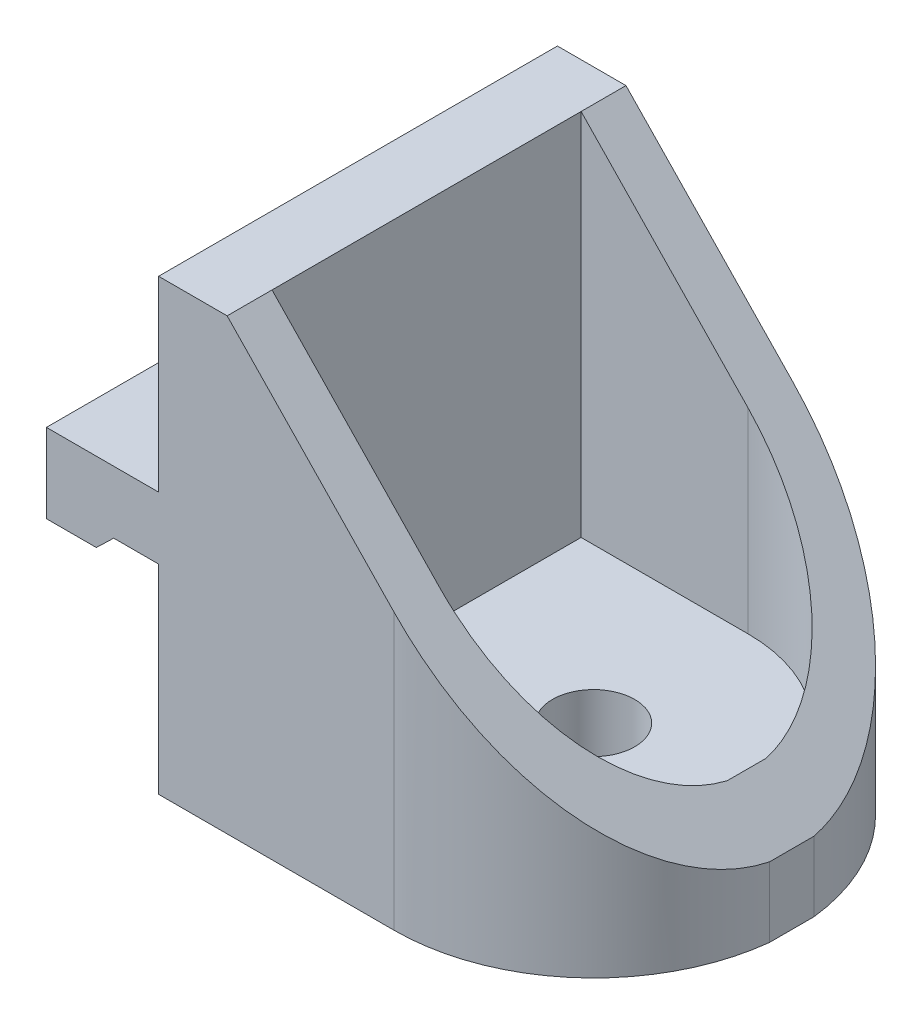
SolidWorks part; units mm, degrees
ref_plane "Front Plane" through (0, 0, 0) normal (0, 0, 1) x (1, 0, 0)
ref_plane "Top Plane" through (0, 0, 0) normal (0, 1, 0) x (1, 0, 0)
ref_plane "Right Plane" through (0, 0, 0) normal (1, 0, 0) x (0, 0, -1)
sketch "Sketch1" plane through (0, 0, 0) normal (0, 0, 1) x (1, 0, 0)
  line L0 (15.9, 0) -> (-18.9, 0)
  line L1 (-18.9, 0) -> (-18.9, 16)
  line L7 (-18.9, 21) -> (-18.9, 36)
  line L8 (-18.9, 36) -> (-13.4, 36)
  line L9 (-13.4, 36) -> (15.9, 5.6)
  line L10 (15.9, 5.6) -> (15.9, 0)
  line L11 (-4.5, 0) -> (4.5, 0) construction
  line L12 (-18.9, 21) -> (-27.9, 21)
  line L13 (-27.9, 21) -> (-27.9, 14.6507)
  line L14 (-27.9, 14.6507) -> (-23.9, 14.6507)
  line L15 (-23.9, 14.6507) -> (-22.5, 16)
  line L16 (-22.5, 16) -> (-18.9, 16)
  point P3 (4.5, 0)
  point P13 (-4.5, 0)
  dimension "D1" = 11.4
  dimension "D2" = 9
  dimension "D3" = 14.4
  dimension "D4" = 36
  dimension "D5" = 5
  dimension "D6" = 9
  dimension "D7" = 4
  dimension "D8" = 5.4
  dimension "D9" = 15
  dimension "D11" = 5.6
  dimension "D12" = 5.5
extrude "Boss-Extrude1" add sketch "Sketch1" along normal mid plane 32
sketch "Sketch2" plane through (0, 0, 0) normal (0, -1, 0) x (1, 0, 0)
  line L0 (-18.9, 16) -> (15.9, 16) construction
  line L1 (-18.9, -16) -> (15.9, -16) construction
  line L2 (0, 16) -> (0, 22.3972)
  line L3 (0, 22.3972) -> (24.6333, 22.3972)
  line L4 (24.6333, 22.3972) -> (24.6333, -22.9363)
  line L5 (24.6333, -22.9363) -> (0, -22.9363)
  line L6 (0, -22.9363) -> (0, -16)
  arc A0 (0, 16) -> (0, -16) centre (0, 0) cw
extrude "Cut-Extrude1" cut sketch "Sketch2" against normal through all
sketch "Sketch3" plane through (0, 0, 0) normal (0, 1, 0) x (1, 0, 0)
  line L0 (-13.4, -16) -> (-13.4, 16) construction
  line L1 (-13.4, -12.4) -> (-13.4, 12.4)
  line L13 (12.3, -1.5716) -> (12.3, 1.5716)
  line L14 (-13.4, -12.4) -> (0, -12.4)
  line L15 (0, 12.4) -> (-13.4, 12.4)
  line L16 (12.3, -1.5716) -> (12.3, 1.5716)
  line L17 (-13.4, -12.4) -> (0, -12.4)
  line L18 (0, 12.4) -> (-13.4, 12.4)
  arc A9 (0, -12.4) -> (12.3, -1.5716) centre (0, 0) ccw
  arc A10 (12.3, 1.5716) -> (0, 12.4) centre (0, 0) ccw
  arc A11 (0, -12.4) -> (12.3, -1.5716) centre (0, 0) ccw
  arc A12 (12.3, 1.5716) -> (0, 12.4) centre (0, 0) ccw
  dimension "D1" = 3.6
extrude "Cut-Extrude2" cut sketch "Sketch3" along normal through all from offset 6.4
sketch "Sketch4" plane through (0, 0, 0) normal (0, 1, 0) x (1, 0, 0)
  circle A0 centre (0, 0) radius 3.2986
extrude "Cut-Extrude3" cut sketch "Sketch4" along normal through all
